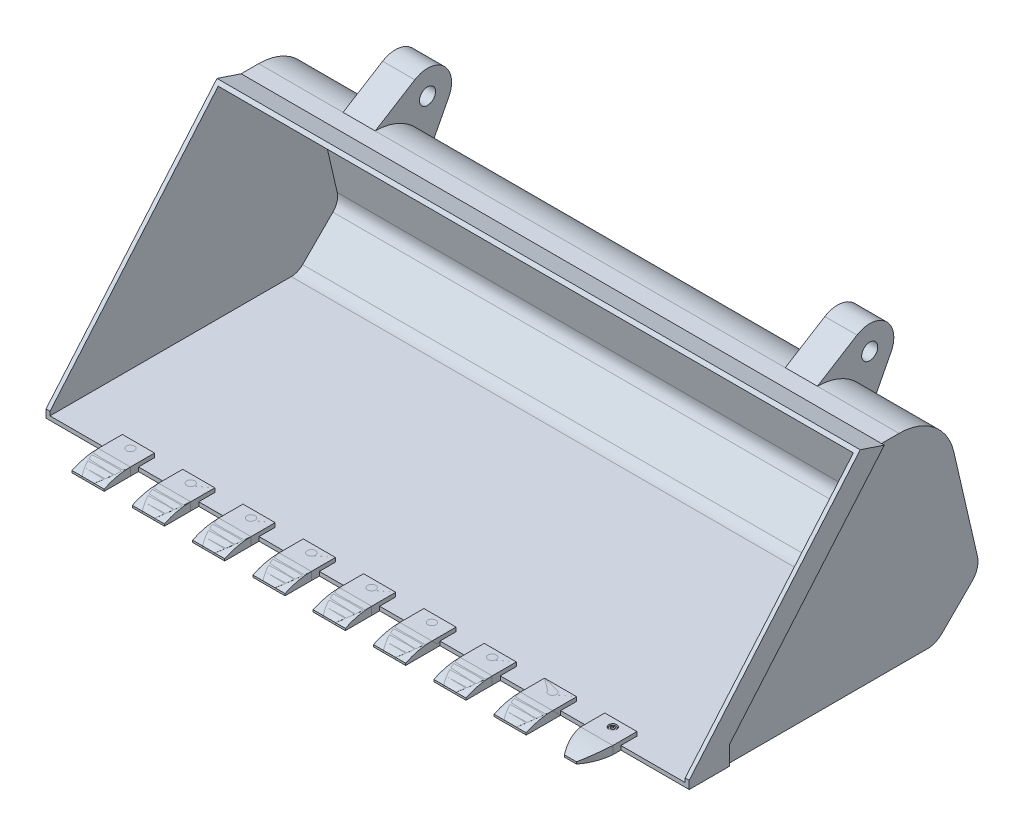
SolidWorks part; units mm, degrees
ref_plane "Front Plane" through (0, 0, 0) normal (0, 0, 1) x (1, 0, 0)
ref_plane "Top Plane" through (0, 0, 0) normal (0, 1, 0) x (1, 0, 0)
ref_plane "Right Plane" through (0, 0, 0) normal (1, 0, 0) x (0, 0, -1)
sketch "Sketch2" plane through (0, 0, 0) normal (1, 0, 0) x (0, 0, -1)
  line L0 (125.3318, 519.3496) -> (-300, 20)
  line L1 (-300, 20) -> (-300, 0)
  line L2 (-300, 0) -> (300, 0)
  line L3 (335.3553, 14.6447) -> (410.7144, 90.0038)
  line L4 (424.0776, 136.6067) -> (365.3826, 390.8427)
  line L5 (228.9708, 499.3496) -> (185.3318, 499.3496)
  line L6 (185.3318, 499.3496) -> (125.3318, 519.3496)
  arc A0 (410.7144, 90.0038) -> (424.0776, 136.6067) centre (375.3591, 125.3591) ccw
  arc A1 (300, 0) -> (335.3553, 14.6447) centre (300, 50) ccw
  arc A2 (365.3826, 390.8427) -> (228.9708, 499.3496) centre (228.9708, 359.3496) ccw
  point P12 (430.3122, 109.6016)
  point P15 (320.7107, 0)
  point P18 (340.3318, 499.3496)
  dimension "D7" = 50
  dimension "D11" = 140
  dimension "D1" = 20
  dimension "D2" = 135
  dimension "D3" = 122
  dimension "D4" = 155
  dimension "D5" = 400
  dimension "D6" = 155
  dimension "D8" = 20
  dimension "D9" = 60
  dimension "D10" = 600
extrude "Boss-Extrude1" add sketch "Sketch2" along normal mid plane 1600
sketch "Sketch3" plane through (0, 0, 0) normal (1, 0, 0) x (0, 0, -1)
  line L0 (118.3388, 511.1396) -> (-308.5177, 10)
  line L1 (-308.5177, 10) -> (-290, 10)
  line L7 (128.5699, 507.7293) -> (118.3388, 511.1396)
  line L8 (125.3318, 519.3496) -> (-300, 20) construction
  line L14 (183.709, 489.3496) -> (128.5699, 507.7293)
  line L15 (128.5699, 507.7293) -> (-290, 16.3184)
  line L16 (-290, 16.3184) -> (-290, 10)
  line L17 (-290, 10) -> (300, 10)
  line L18 (328.2843, 21.7157) -> (403.6434, 97.0748)
  line L19 (414.3339, 134.3571) -> (355.6389, 388.5932)
  line L20 (228.9708, 489.3496) -> (183.709, 489.3496)
  line L21 (183.709, 489.3496) -> (128.5699, 507.7293)
  line L24 (-290, 10) -> (300, 10)
  line L25 (328.2843, 21.7157) -> (403.6434, 97.0748)
  line L26 (414.3339, 134.3571) -> (355.6389, 388.5932)
  line L27 (228.9708, 489.3496) -> (183.709, 489.3496)
  arc A6 (300, 10) -> (328.2843, 21.7157) centre (300, 50) ccw
  arc A7 (403.6434, 97.0748) -> (414.3339, 134.3571) centre (375.3591, 125.3591) ccw
  arc A8 (355.6389, 388.5932) -> (228.9708, 489.3496) centre (228.9708, 359.3496) ccw
  arc A9 (300, 10) -> (328.2843, 21.7157) centre (300, 50) ccw
  arc A10 (403.6434, 97.0748) -> (414.3339, 134.3571) centre (375.3591, 125.3591) ccw
  arc A11 (355.6389, 388.5932) -> (228.9708, 489.3496) centre (228.9708, 359.3496) ccw
  dimension "D1" = 10
extrude "Cut-Extrude1" cut sketch "Sketch3" against normal mid plane 1580
sketch "Sketch4" plane through (800, 0, 0) normal (1, 0, 0) x (0, 0, -1)
  line L0 (185.3318, 499.3496) -> (-200, 46.9609)
  line L1 (-200, 46.9609) -> (-200, 0)
  line L7 (185.3318, 499.3496) -> (125.3318, 519.3496)
  line L8 (125.3318, 519.3496) -> (-300, 20)
  line L9 (-300, 20) -> (-300, 0)
  line L10 (-300, 0) -> (300, 0)
  line L11 (335.3553, 14.6447) -> (410.7144, 90.0038)
  line L12 (424.0776, 136.6067) -> (365.3826, 390.8427)
  line L13 (228.9708, 499.3496) -> (185.3318, 499.3496)
  line L14 (185.3318, 499.3496) -> (125.3318, 519.3496)
  line L15 (125.3318, 519.3496) -> (-300, 20)
  line L16 (-300, 20) -> (-300, 0)
  line L17 (-200, 0) -> (300, 0)
  line L18 (335.3553, 14.6447) -> (410.7144, 90.0038)
  line L19 (424.0776, 136.6067) -> (365.3826, 390.8427)
  line L20 (228.9708, 499.3496) -> (185.3318, 499.3496)
  arc A3 (300, 0) -> (335.3553, 14.6447) centre (300, 50) ccw
  arc A4 (410.7144, 90.0038) -> (424.0776, 136.6067) centre (375.3591, 125.3591) ccw
  arc A5 (365.3826, 390.8427) -> (228.9708, 499.3496) centre (228.9708, 359.3496) ccw
  arc A6 (300, 0) -> (335.3553, 14.6447) centre (300, 50) ccw
  arc A7 (410.7144, 90.0038) -> (424.0776, 136.6067) centre (375.3591, 125.3591) ccw
  arc A8 (365.3826, 390.8427) -> (228.9708, 499.3496) centre (228.9708, 359.3496) ccw
  line M16 (-300, 0) -> (300, 0)
  arc M17 (300, 0) -> (335.3553, 14.6447) centre (300, 50) ccw
  line M18 (335.3553, 14.6447) -> (410.7144, 90.0038)
  arc M19 (410.7144, 90.0038) -> (424.0776, 136.6067) centre (375.3591, 125.3591) ccw
  line M20 (424.0776, 136.6067) -> (365.3826, 390.8427)
  arc M21 (365.3826, 390.8427) -> (228.9708, 499.3496) centre (228.9708, 359.3496) ccw
  line M22 (228.9708, 499.3496) -> (185.3318, 499.3496)
  dimension "D2" = 500
  dimension "D1" = 0
extrude "Cut-Extrude2" cut sketch "Sketch4" against normal blind 7 contours L0 L1 M16 M17 M18 M19 M20 M21 M22
ref_plane "Plane1" through (590, 0, 0) normal (1, 0, 0) x (0, 0, -1)
sketch "Sketch5" plane through (590, 0, 0) normal (1, 0, 0) x (0, 0, -1)
  line L0 (228.9708, 499.3496) -> (327.3558, 560.3446)
  line L1 (412.3015, 481.857) -> (365.3826, 390.8427)
  arc A0 (327.3558, 560.3446) -> (412.3015, 481.857) centre (358.9708, 509.3496) cw
  arc A1 (365.3826, 390.8427) -> (228.9708, 499.3496) centre (228.9708, 359.3496) ccw construction
  arc A2 (365.3826, 390.8427) -> (228.9708, 499.3496) centre (228.9708, 359.3496) ccw
  circle A3 centre (358.9708, 509.3496) radius 20
  dimension "D3" = 40
  dimension "D4" = 60
  dimension "D1" = 130
  dimension "D2" = 150
extrude "Boss-Extrude2" add sketch "Sketch5" against normal blind 80
mirror "Mirror1" about plane through (0, 0, 0) normal (1, 0, 0) of "Boss-Extrude2"
sketch "Sketch6" plane through (590, 0, 0) normal (1, 0, 0) x (0, 0, -1)
  line L0 (-260, 20) -> (-260, 10)
  line L1 (-300, 10) -> (300, 10) construction
  line L2 (-260, 10) -> (-300, 10)
  line L3 (-300, 10) -> (-300, 0)
  line L4 (-300, 0) -> (-385.3835, 0)
  line L5 (-385.3835, 0) -> (-385.3835, 5)
  line L6 (-260, 20) -> (-320, 20)
  arc A0 (-320, 20) -> (-385.3835, 5) centre (-320, -130) ccw
  dimension "D4" = 150
  dimension "D1" = 10
  dimension "D2" = 60
  dimension "D3" = 5
  dimension "D5" = 40
extrude "Boss-Extrude3" add sketch "Sketch6" along normal mid plane 80 separate body
sketch "Sketch7" plane through (0, 20, 0) normal (0, 1, 0) x (1, 0, 0)
  line L0 (630, -260) -> (550, -300) construction
  circle A0 centre (590, -280) radius 6
  dimension "D1" = 12
extrude "Cut-Extrude3" cut sketch "Sketch7" against normal through all
sketch "Sketch9" plane through (0, 20, 0) normal (0, 1, 0) x (1, 0, 0)
  circle A0 centre (590, -280) radius 10
  dimension "D1" = 20
extrude "Cut-Extrude4" cut sketch "Sketch9" against normal blind 10
sketch "Sketch11" plane through (0, 10, 0) normal (0, 1, 0) x (1, 0, 0)
  circle A0 centre (590, -280) radius 8.5
  dimension "D1" = 17
extrude "Boss-Extrude4" add sketch "Sketch11" along normal blind 8 separate body
fillet "Fillet1" radius 1 1 edges at (590, 18, 288.5)
sketch "Sketch12" plane through (0, 10, 0) normal (0, 1, 0) x (1, 0, 0)
  circle A0 centre (590, -280) radius 6
  dimension "D1" = 12
extrude "Boss-Extrude5" add sketch "Sketch12" against normal blind 8 separate body
sketch "Sketch13" plane through (0, 18, 0) normal (0, 1, 0) x (1, 0, 0)
  line L1 (587.3869, -284.8396) -> (592.8846, -284.6828)
  line L2 (592.8846, -284.6828) -> (595.4978, -279.8433)
  line L3 (595.4978, -279.8433) -> (592.6131, -275.1604)
  line L4 (592.6131, -275.1604) -> (587.1154, -275.3172)
  line L5 (587.1154, -275.3172) -> (584.5022, -280.1567)
  line L6 (584.5022, -280.1567) -> (587.3869, -284.8396)
  circle A0 centre (590, -280) radius 4.7631 construction
  dimension "D1" = 5.5
extrude "Cut-Extrude5" cut sketch "Sketch13" against normal blind 4
sketch "Sketch15" plane through (0, 0, 0) normal (0, -1, 0) x (1, 0, 0)
  line L0 (541.2368, 321.2856) -> (550, 320)
  line L1 (630, 385.3835) -> (550, 385.3835) construction
  line L2 (575, 385.3835) -> (605, 385.3835)
  line L3 (646.9165, 321.1682) -> (630, 320)
  line L4 (590, 391.432) -> (590, 309.9077) construction
  line L5 (590, -314.6718) -> (590, 314.6718) construction
  arc A0 (550, 320) -> (575, 385.3835) centre (709.0089, 296.6727) cw
  arc A1 (630, 320) -> (605, 385.3835) centre (510.4002, 311.7411) ccw
  line M7 (550, 385.3835) -> (550, 300)
  line M9 (630, 300) -> (630, 385.3835)
  line M10 (630, 385.3835) -> (550, 385.3835)
  dimension "D1" = 30
extrude "Cut-Extrude8" cut sketch "Sketch15" against normal through all and the other way through all contours A0 M7 M10 | A1 M9 M10
pattern_linear "LPattern2" count 9 spacing 150 along (-1, 0, 0) of bodies 117 129
pattern_linear "LPattern1" count 9 spacing 150 along (-1, 0, 0) of "Boss-Extrude3"
